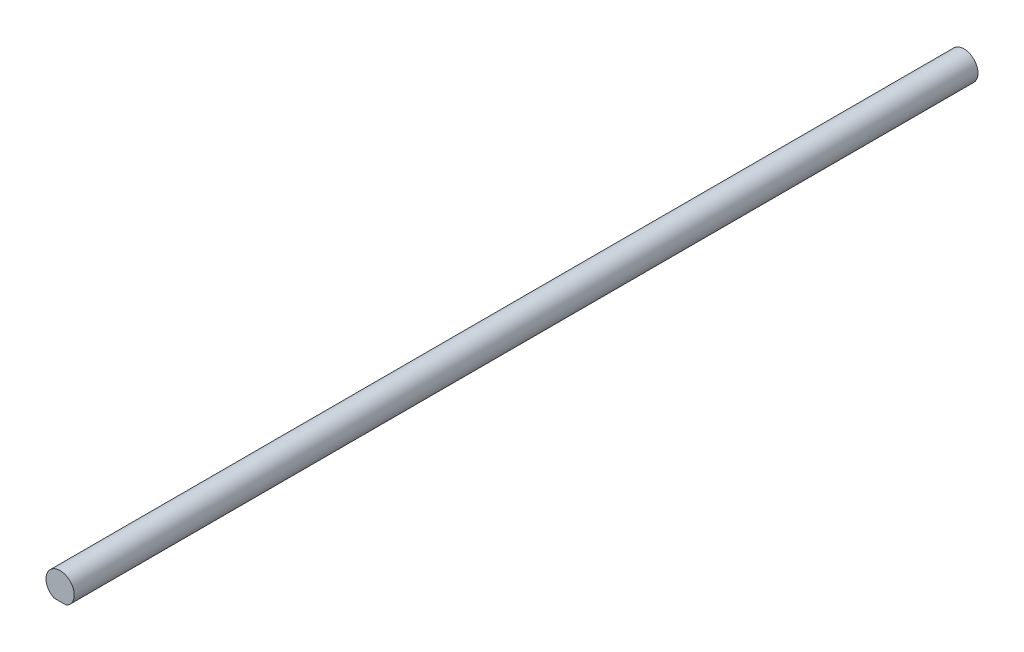
SolidWorks part; units mm, degrees
ref_plane "Front Plane" through (0, 0, 0) normal (0, 0, 1) x (1, 0, 0)
ref_plane "Top Plane" through (0, 0, 0) normal (0, 1, 0) x (1, 0, 0)
ref_plane "Right Plane" through (0, 0, 0) normal (1, 0, 0) x (0, 0, -1)
sketch "Sketch1" plane through (0, 0, 0) normal (0, 0, 1) x (1, 0, 0)
  line L0 (-1.384, -2.8575) -> (1.384, -2.8575)
  arc A0 (1.384, -2.8575) -> (-1.384, -2.8575) centre (0, 0) ccw
  dimension "D1" = 6.35
  dimension "D2" = 2.8575
extrude "Boss-Extrude1" add sketch "Sketch1" along normal blind 203.2
